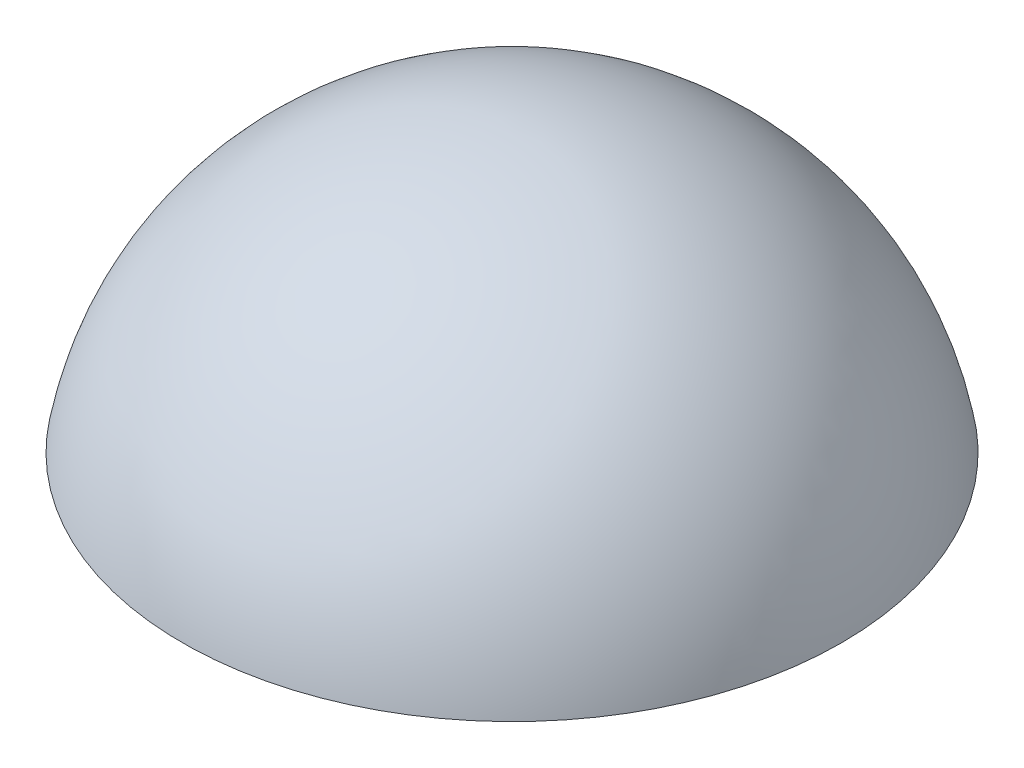
SolidWorks part; units mm, degrees
ref_plane "Front Plane" through (0, 0, 0) normal (0, 0, 1) x (1, 0, 0)
ref_plane "Top Plane" through (0, 0, 0) normal (0, 1, 0) x (1, 0, 0)
ref_plane "Right Plane" through (0, 0, 0) normal (1, 0, 0) x (0, 0, -1)
sketch "Sketch1" plane through (0, 0, 0) normal (0, 0, 1) x (1, 0, 0)
  line L0 (0, 30) -> (0, 5.72)
  line L1 (0, 5.72) -> (29.4496, 5.72)
  arc A0 (0, 30) -> (29.4496, 5.72) centre (0, 0) cw
  dimension "D1" = 30
  dimension "D2" = 24.28
revolve "Revolve1" add sketch "Sketch1" angle 360 about L0
shell "Shell1" thickness 3
sketch "Sketch2" plane through (0, 0, 0) normal (1, 0, 0) x (0, 0, -1)
  circle A0 centre (0, 0) radius 10
  dimension "D1" = 20
extrude "Cut-Extrude1" cut sketch "Sketch2" against normal up to next
